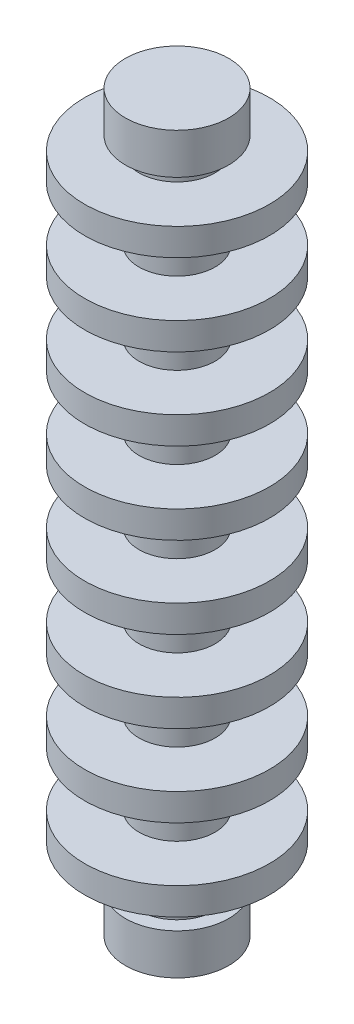
SolidWorks part; units mm, degrees
ref_plane "Front Plane" through (0, 0, 0) normal (0, 0, 1) x (1, 0, 0)
ref_plane "Top Plane" through (0, 0, 0) normal (0, 1, 0) x (1, 0, 0)
ref_plane "Right Plane" through (0, 0, 0) normal (1, 0, 0) x (0, 0, -1)
sketch "Sketch1" plane through (0, 0, 0) normal (0, 0, 1) x (1, 0, 0)
  line L0 (0, -24) -> (0, 24) construction
  line L1 (2.8, 24) -> (2.8, 23)
  line L2 (-20.9325, 24) -> (2.8, 24) construction
  line L3 (2.8, 18) -> (2.8, 17)
  line L4 (2.8, 17) -> (6.8, 17)
  line L5 (2.8, 23) -> (6.8, 23)
  line L6 (6.8, 23) -> (6.8, 21)
  line L7 (6.8, 21) -> (2.8, 21)
  line L8 (2.8, 21) -> (2.8, 18)
  line L9 (2.8, 24) -> (3.8, 24)
  line L10 (3.8, 24) -> (3.8, 27)
  line L11 (3.8, 27) -> (0, 27)
  line L12 (0, 0) -> (33.9437, 0) construction
  line L13 (6.8, 17) -> (6.8, 15)
  line L14 (6.8, 15) -> (2.8, 15)
  line L15 (2.8, 15) -> (2.8, 12)
  line L16 (0, 27) -> (0, -27)
  line L17 (3.8, -27) -> (0, -27)
  line L18 (3.8, -24) -> (3.8, -27)
  line L19 (2.8, -24) -> (3.8, -24)
  line L20 (2.8, 12) -> (2.8, 11)
  line L21 (2.8, 11) -> (6.8, 11)
  line L22 (6.8, 11) -> (6.8, 9)
  line L23 (6.8, 9) -> (2.8, 9)
  line L24 (2.8, 9) -> (2.8, 6)
  line L29 (2.8, 6) -> (2.8, 5)
  line L30 (2.8, 5) -> (6.8, 5)
  line L31 (6.8, 5) -> (6.8, 3)
  line L32 (6.8, 3) -> (2.8, 3)
  line L33 (2.8, 3) -> (2.8, 0)
  line L38 (2.8, 0) -> (2.8, -1)
  line L39 (2.8, -1) -> (6.8, -1)
  line L40 (6.8, -1) -> (6.8, -3)
  line L41 (6.8, -3) -> (2.8, -3)
  line L42 (2.8, -3) -> (2.8, -6)
  line L47 (2.8, -6) -> (2.8, -7)
  line L48 (2.8, -7) -> (6.8, -7)
  line L49 (6.8, -7) -> (6.8, -9)
  line L50 (6.8, -9) -> (2.8, -9)
  line L51 (2.8, -9) -> (2.8, -12)
  line L56 (2.8, -12) -> (2.8, -13)
  line L57 (2.8, -13) -> (6.8, -13)
  line L58 (6.8, -13) -> (6.8, -15)
  line L59 (6.8, -15) -> (2.8, -15)
  line L60 (2.8, -15) -> (2.8, -18)
  line L65 (2.8, -18) -> (2.8, -19)
  line L66 (2.8, -19) -> (6.8, -19)
  line L67 (6.8, -19) -> (6.8, -21)
  line L68 (6.8, -21) -> (2.8, -21)
  line L69 (2.8, -21) -> (2.8, -24)
  point P4 (0, 0)
  dimension "D1" = 48
  dimension "D2" = 2.8
  dimension "D3" = 3.8
  dimension "D4" = 3
  dimension "D7" = 2
  dimension "D11" = 4
  dimension "D12" = 8
revolve "Revolve1" add sketch "Sketch1" angle 360 about L16
